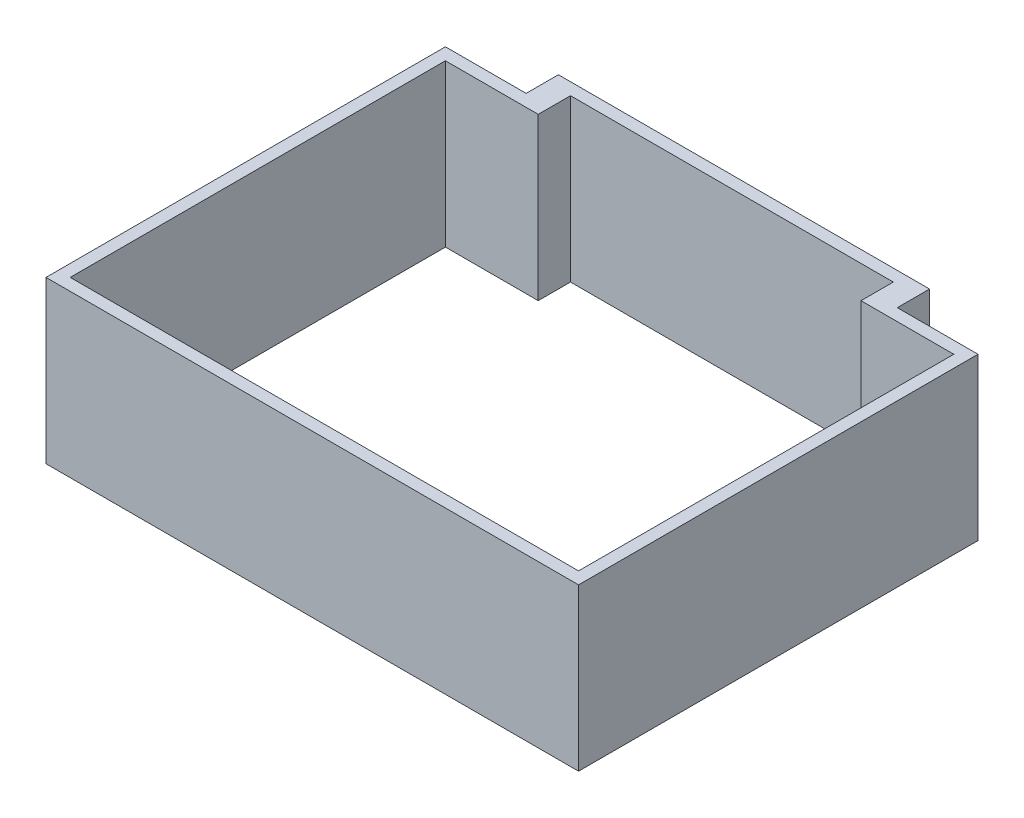
SolidWorks part; units mm, degrees
ref_plane "前视基准面" through (0, 0, 0) normal (0, 0, 1) x (1, 0, 0)
ref_plane "上视基准面" through (0, 0, 0) normal (0, 1, 0) x (1, 0, 0)
ref_plane "右视基准面" through (0, 0, 0) normal (1, 0, 0) x (0, 0, -1)
other "Configuration Table"
sketch "草图2" plane through (0, 0, 0) normal (0, 0, 1) x (1, 0, 0)
  line L0 (-33, -10) -> (-31.5, -10)
  line L1 (-31.5, -10) -> (-31.5, 10)
  line L2 (-31.5, 10) -> (-33, 10)
  line L3 (-33, 10) -> (-33, -10)
  line L4 (31.5, -10) -> (33, -10)
  line L5 (33, -10) -> (33, 10)
  line L6 (33, 10) -> (31.5, 10)
  line L7 (31.5, 10) -> (31.5, -10)
sketch "草图3" plane through (0, 0, 0) normal (0, 0, 1) x (1, 0, 0)
  line L0 (-33, -10) -> (33, -10)
  line L1 (33, -10) -> (33, 10)
  line L2 (33, 10) -> (-33, 10)
  line L3 (-33, 10) -> (-33, -10)
sketch "草图4" plane through (0, 0, 0) normal (0, 0, 1) x (1, 0, 0)
  line L0 (-22, -10) -> (22, -10)
  line L1 (22, -10) -> (22, 10)
  line L2 (22, 10) -> (-22, 10)
  line L3 (-22, 10) -> (-22, -10)
extrude "主板上方下横带" add sketch "草图4" along normal blind 1.5
sketch "草图5" plane through (0, 0, 0) normal (0, 0, 1) x (1, 0, 0)
  line L0 (-23, -10) -> (-20, -10)
  line L1 (-20, -10) -> (-20, 10)
  line L2 (-20, 10) -> (-23, 10)
  line L3 (-23, 10) -> (-23, -10)
extrude "绕螺钉抬升段_-1" add sketch "草图5" along normal blind 5.5
sketch "草图6" plane through (0, 0, 0) normal (0, 0, 1) x (1, 0, 0)
  line L0 (-33, -10) -> (-21, -10)
  line L1 (-21, -10) -> (-21, 10)
  line L2 (-21, 10) -> (-33, 10)
  line L3 (-33, 10) -> (-33, -10)
extrude "螺钉头上方跨带_-1" add sketch "草图6" along normal blind 1.5 from offset 4
sketch "草图7" plane through (0, 0, 0) normal (0, 0, 1) x (1, 0, 0)
  line L0 (-33, -10) -> (-31.5, -10)
  line L1 (-31.5, -10) -> (-31.5, 10)
  line L2 (-31.5, 10) -> (-33, 10)
  line L3 (-33, 10) -> (-33, -10)
extrude "绑带外侧立段_-1" add sketch "草图7" along normal blind 48 from offset 4
sketch "草图8" plane through (0, 0, 0) normal (0, 0, 1) x (1, 0, 0)
  line L0 (20, -10) -> (23, -10)
  line L1 (23, -10) -> (23, 10)
  line L2 (23, 10) -> (20, 10)
  line L3 (20, 10) -> (20, -10)
extrude "绕螺钉抬升段_1" add sketch "草图8" along normal blind 5.5
sketch "草图9" plane through (0, 0, 0) normal (0, 0, 1) x (1, 0, 0)
  line L0 (21, -10) -> (33, -10)
  line L1 (33, -10) -> (33, 10)
  line L2 (33, 10) -> (21, 10)
  line L3 (21, 10) -> (21, -10)
extrude "螺钉头上方跨带_1" add sketch "草图9" along normal blind 1.5 from offset 4
sketch "草图10" plane through (0, 0, 0) normal (0, 0, 1) x (1, 0, 0)
  line L0 (31.5, -10) -> (33, -10)
  line L1 (33, -10) -> (33, 10)
  line L2 (33, 10) -> (31.5, 10)
  line L3 (31.5, 10) -> (31.5, -10)
extrude "绑带外侧立段_1" add sketch "草图10" along normal blind 48 from offset 4
sketch "草图11" plane through (0, 0, 0) normal (0, 0, 1) x (1, 0, 0)
  line L0 (-33, -10) -> (33, -10)
  line L1 (33, -10) -> (33, 10)
  line L2 (33, 10) -> (-33, 10)
  line L3 (-33, 10) -> (-33, -10)
extrude "电池上横带" add sketch "草图11" along normal blind 1.5 from offset 52
